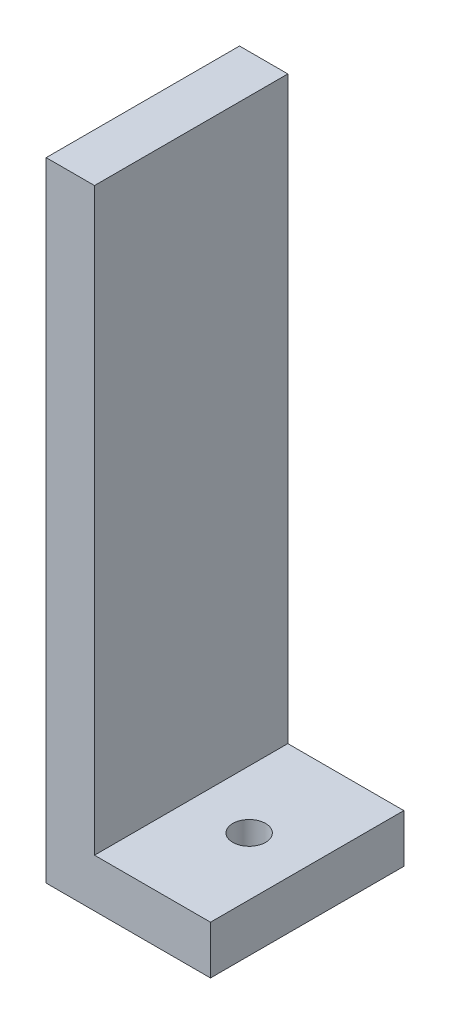
SolidWorks part; units mm, degrees
ref_plane "Ön Düzlem" through (0, 0, 0) normal (0, 0, 1) x (1, 0, 0)
ref_plane "Üst Düzlem" through (0, 0, 0) normal (0, 1, 0) x (1, 0, 0)
ref_plane "Sağ Düzlem" through (0, 0, 0) normal (1, 0, 0) x (0, 0, -1)
sketch "Çizim1" plane through (0, 0, 0) normal (0, 0, 1) x (1, 0, 0)
  line L0 (0, 0) -> (12, 0)
  line L1 (0, 0) -> (0, 60)
  line L2 (0, 60) -> (-5, 60)
  line L3 (-5, 60) -> (-5, -5)
  line L4 (-5, -5) -> (12, -5)
  line L5 (12, -5) -> (12, 0)
  dimension "D1" = 12
  dimension "D2" = 17
  dimension "D3" = 5
  dimension "D4" = 5
  dimension "D5" = 65
extrude "Yükseklik-Ekstrüzyon1" add sketch "Çizim1" along normal blind 20
sketch "Çizim2" plane through (0, 0, 0) normal (0, 1, 0) x (1, 0, 0)
  circle A0 centre (6, -10) radius 1.7
extrude "Kes-Ekstrüzyon1" cut sketch "Çizim2" against normal blind 20
